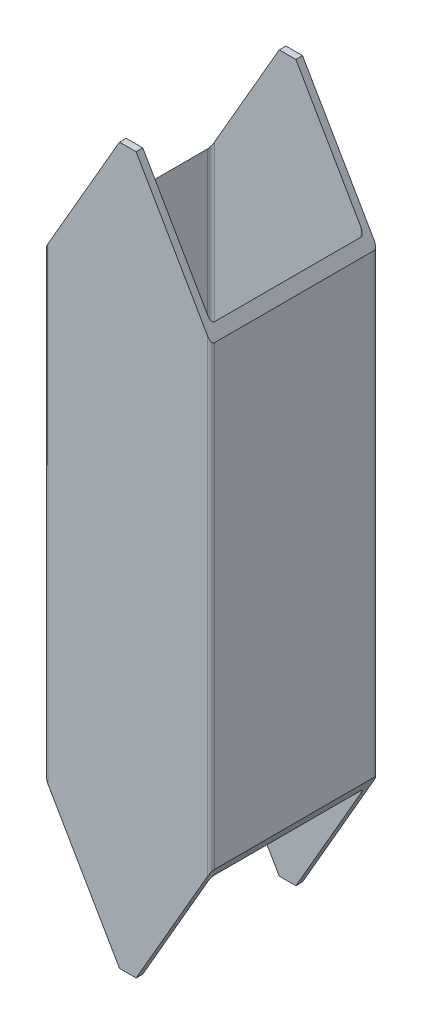
SolidWorks part; units mm, degrees
ref_plane "Plan de face" through (0, 0, 0) normal (0, 0, 1) x (1, 0, 0)
ref_plane "Plan de dessus" through (0, 0, 0) normal (0, 1, 0) x (1, 0, 0)
ref_plane "Plan de droite" through (0, 0, 0) normal (1, 0, 0) x (0, 0, -1)
sketch "Esquisse2" plane through (0, 0, 0) normal (0, 1, 0) x (1, 0, 0)
  line L0 (6, 96) -> (94, 96)
  line L1 (2, 0) -> (98, 0)
  line L2 (0, 2) -> (0, 98)
  line L3 (2, 100) -> (98, 100)
  line L4 (100, 2) -> (100, 98)
  line L5 (96, 6) -> (96, 94)
  line L6 (6, 4) -> (94, 4)
  line L7 (4, 6) -> (4, 94)
  line L8 (4, 4) -> (4, 96) construction
  line L9 (4, 96) -> (96, 96) construction
  line L10 (96, 4) -> (96, 96) construction
  line L11 (4, 4) -> (96, 4) construction
  line L12 (0, 0) -> (0, 100) construction
  line L13 (0, 0) -> (100, 0) construction
  line L14 (100, 0) -> (100, 100) construction
  line L15 (0, 100) -> (100, 100) construction
  arc A0 (4, 94) -> (6, 96) centre (6, 94) cw
  arc A1 (96, 6) -> (94, 4) centre (94, 6) cw
  arc A2 (6, 4) -> (4, 6) centre (6, 6) cw
  arc A3 (0, 2) -> (2, 0) centre (2, 2) ccw
  arc A4 (98, 0) -> (100, 2) centre (98, 2) ccw
  arc A5 (96, 94) -> (94, 96) centre (94, 94) ccw
  arc A6 (100, 98) -> (98, 100) centre (98, 98) ccw
  arc A7 (2, 100) -> (0, 98) centre (2, 98) ccw
  point P21 (0, 0)
  dimension "D4" = 2
  dimension "D1" = 100
  dimension "D2" = 100
  dimension "D3" = 4
extrude "Boss.-Extru.1" add sketch "Esquisse2" along normal blind 430
sketch "Esquisse3" plane through (0, 0, 0) normal (0, 0, 1) x (1, 0, 0)
  line L0 (50, 430) -> (45, 430) construction
  line L1 (2, 430) -> (98, 430) construction
  line L2 (45, 430) -> (0, 352.0577)
  line L3 (0, 430) -> (0, 0) construction
  line L4 (0, 352.0577) -> (-62.4502, 352.0577)
  line L5 (-62.4502, 352.0577) -> (-62.4502, 486.3017)
  line L6 (-62.4502, 486.3017) -> (45, 486.3017)
  line L7 (45, 486.3017) -> (45, 430)
  line L8 (45, 430) -> (0, 430) construction
  line L9 (0, 430) -> (0, 352.0577) construction
  line L10 (50, 0) -> (50, 430) construction
  line L11 (2, 0) -> (98, 0) construction
  line L12 (45, 430) -> (45, 0) construction
  line L13 (45, 0) -> (0, 77.9423)
  line L14 (0, 77.9423) -> (-44.1973, 77.9423)
  line L15 (-44.1973, 77.9423) -> (-44.1973, -11.8307)
  line L16 (-44.1973, -11.8307) -> (45, -11.8307)
  line L17 (45, -11.8307) -> (45, 0)
  line L18 (55, -11.8307) -> (55, 0)
  line L19 (144.1973, -11.8307) -> (55, -11.8307)
  line L20 (144.1973, 77.9423) -> (144.1973, -11.8307)
  line L21 (100, 77.9423) -> (144.1973, 77.9423)
  line L22 (55, 0) -> (100, 77.9423)
  line L23 (100, 430) -> (100, 352.0577) construction
  line L24 (55, 430) -> (100, 430) construction
  line L25 (55, 486.3017) -> (55, 430)
  line L26 (162.4502, 486.3017) -> (55, 486.3017)
  line L27 (162.4502, 352.0577) -> (162.4502, 486.3017)
  line L28 (100, 352.0577) -> (162.4502, 352.0577)
  line L29 (55, 430) -> (100, 352.0577)
  dimension "D1" = 5
  dimension "D2" = 60
  dimension "D3" = 60
extrude "Enlèv. mat.-Extru.1" cut sketch "Esquisse3" against normal through all
